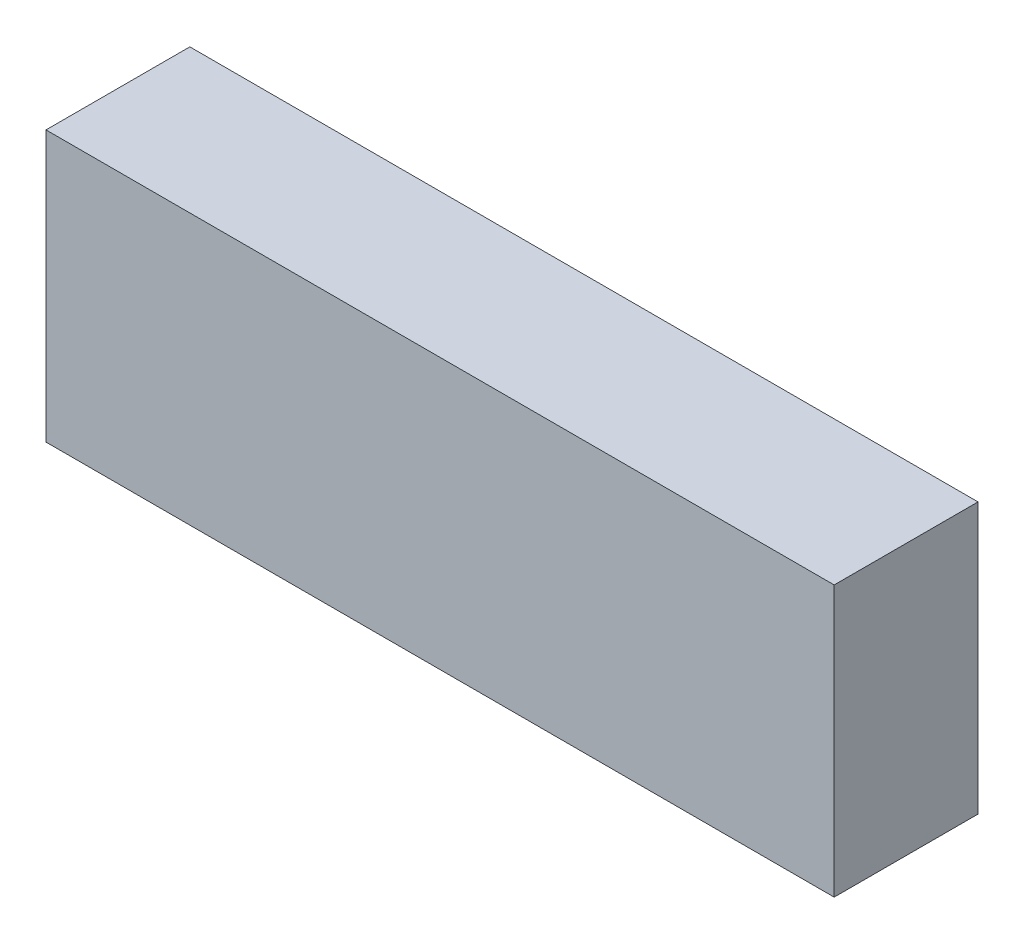
SolidWorks part; units mm, degrees
ref_plane "Front Plane" through (0, 0, 0) normal (0, 0, 1) x (1, 0, 0)
ref_plane "Top Plane" through (0, 0, 0) normal (0, 1, 0) x (1, 0, 0)
ref_plane "Right Plane" through (0, 0, 0) normal (1, 0, 0) x (0, 0, -1)
sketch "Sketch1" plane through (0, 0, 0) normal (0, 0, 1) x (1, 0, 0)
  line L1 (-72.9458, 65.3997) -> (64.0542, 65.3997)
  line L2 (-72.9458, 65.3997) -> (-72.9458, 18.3997)
  line L3 (-72.9458, 18.3997) -> (64.0542, 18.3997)
  line L4 (64.0542, 65.3997) -> (64.0542, 18.3997)
  line L5 (-72.9458, 65.3997) -> (64.0542, 18.3997) construction
  line L6 (-72.9458, 18.3997) -> (64.0542, 65.3997) construction
  point P0 (-4.4458, 41.8997)
  dimension "D1" = 137
  dimension "D2" = 47
extrude "Boss-Extrude1" add sketch "Sketch1" along normal blind 25
